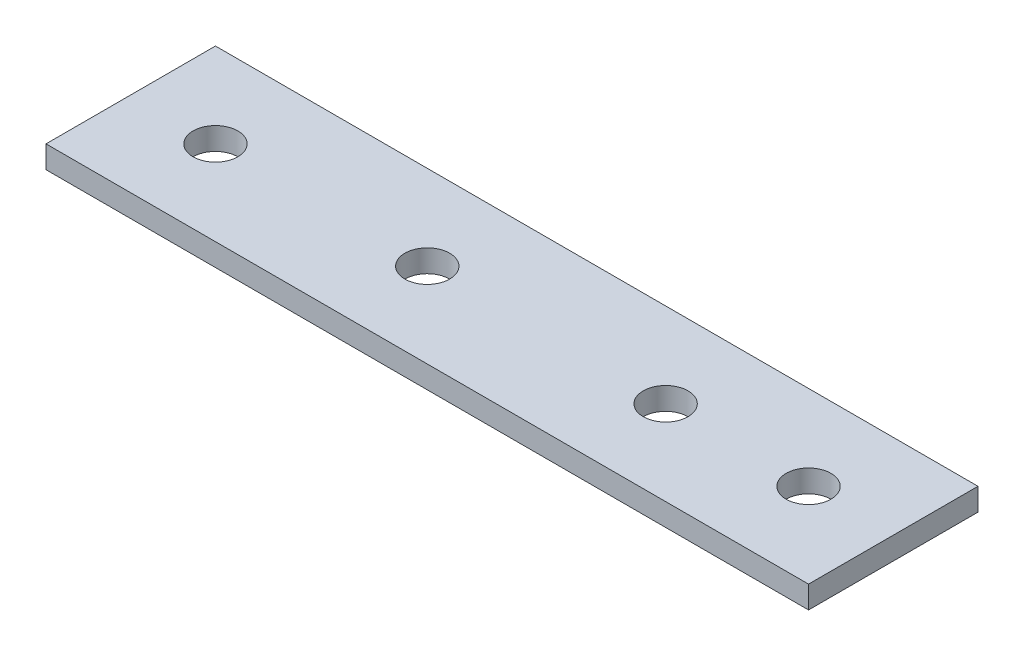
SolidWorks part; units mm, degrees
ref_plane "Front Plane" through (0, 0, 0) normal (0, 0, 1) x (1, 0, 0)
ref_plane "Top Plane" through (0, 0, 0) normal (0, 1, 0) x (1, 0, 0)
ref_plane "Right Plane" through (0, 0, 0) normal (1, 0, 0) x (0, 0, -1)
sketch "Sketch1" plane through (0, 0, 0) normal (0, 1, 0) x (1, 0, 0)
  line L0 (-21, 0) -> (21, 0) construction
  line L1 (27, -6) -> (-27, -6)
  line L2 (27, -6) -> (27, 6)
  line L3 (27, 6) -> (-27, 6)
  line L4 (-27, -6) -> (-27, 6)
  line L5 (27, -6) -> (-27, 6) construction
  line L6 (27, 6) -> (-27, -6) construction
  circle A0 centre (-21, 0) radius 1.5875
  circle A1 centre (21, 0) radius 1.5875
  circle A2 centre (-21, 0) radius 5 construction
  circle A3 centre (-6, 0) radius 1.5875
  circle A4 centre (10.88, 0) radius 1.5875
  point P0 (0, 0)
  point P8 (0, 0)
  point P18 (0, 0)
  dimension "D1" = 3.175
  dimension "D4" = 10
  dimension "D7" = 31.88
  dimension "D2" = 42
  dimension "D3" = 12
  dimension "D5" = 6
  dimension "D6" = 15
extrude "Boss-Extrude1" add sketch "Sketch1" along normal mid plane 1.5875
